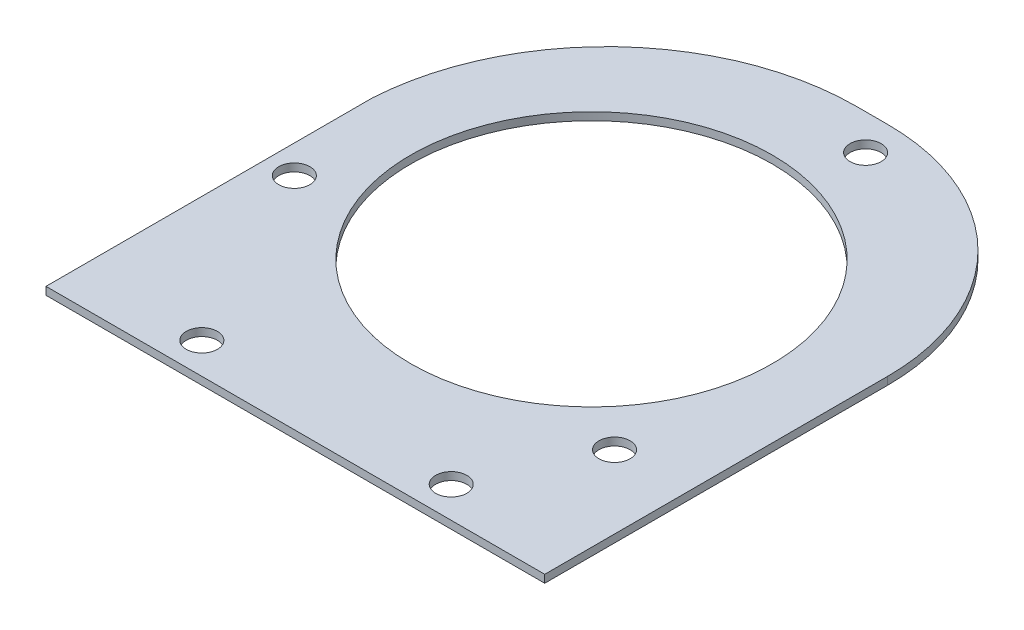
SolidWorks part; units mm, degrees
ref_plane "Front Plane" through (0, 0, 0) normal (0, 0, 1) x (1, 0, 0)
ref_plane "Top Plane" through (0, 0, 0) normal (0, 1, 0) x (1, 0, 0)
ref_plane "Right Plane" through (0, 0, 0) normal (1, 0, 0) x (0, 0, -1)
sketch "Sketch1" plane through (0, 0, 0) normal (0, 1, 0) x (1, 0, 0)
  line L0 (0, 114.3) -> (0, -114.3) construction
  line L1 (12.7, 114.3) -> (0, 114.3)
  line L2 (101.6, 25.4) -> (101.6, -114.3)
  line L3 (101.6, -114.3) -> (-101.6, -114.3)
  line L4 (-101.6, 18.6765) -> (-101.6, -114.3)
  line L5 (101.6, 114.3) -> (-101.6, -114.3) construction
  line L6 (101.6, -114.3) -> (-101.6, 114.3) construction
  line L7 (-101.6, 6.35) -> (101.6, 6.35) construction
  line L8 (0, 6.35) -> (-101.6, -28.6337) construction
  line L9 (-101.6, -101.6) -> (101.6, -101.6) construction
  circle A0 centre (0, 6.35) radius 73.66
  circle A1 centre (0, 6.35) radius 95.25 construction
  circle A2 centre (-90.0606, -24.6604) radius 6.35
  circle A3 centre (-50.8, -101.6) radius 6.35
  circle A4 centre (50.8, -101.6) radius 6.35
  circle A5 centre (18.1746, 99.85) radius 6.35
  circle A6 centre (71.8861, -56.1396) radius 6.35
  arc A7 (0, 114.3) -> (-101.6, 18.6765) centre (0, 12.5132) ccw
  arc A8 (12.7, 114.3) -> (101.6, 25.4) centre (12.7, 25.4) cw
  point P0 (0, 0)
  point P11 (0, 6.35)
  point P30 (0, 6.35)
  point P32 (0, 6.35)
  dimension "D3" = 147.32
  dimension "D5" = 190.5
  dimension "D6" = 12.7
  dimension "D7" = 12.7
  dimension "D8" = 12.7
  dimension "D11" = 88.9
  dimension "D1" = 228.6
  dimension "D2" = 120.65
  dimension "D4" = 19
  dimension "D9" = 50.8
  dimension "D10" = 203.2
extrude "Boss-Extrude1" add sketch "Sketch1" along normal blind 3.175
sketch "Sketch2" plane through (0, 3.175, 0) normal (0, 1, 0) x (1, 0, 0)
  line L0 (-101.6, 18.6765) -> (-101.6, -114.3) construction
  line L2 (101.6, -167.64) -> (-101.6, -167.64)
  line L5 (101.6, -167.64) -> (101.6, 114.3)
  line L6 (101.6, 114.3) -> (-101.6, 114.3)
  line L7 (-101.6, -114.3) -> (101.6, -114.3) construction
  line L8 (101.6, -114.3) -> (101.6, 25.4) construction
  line L9 (12.7, 114.3) -> (0, 114.3) construction
  line L10 (-101.6, 18.6765) -> (-101.6, -114.3)
  line L11 (-101.6, -114.3) -> (101.6, -114.3)
  line L12 (101.6, -114.3) -> (101.6, 25.4)
  line L13 (12.7, 114.3) -> (0, 114.3)
  line L14 (-101.6, -167.64) -> (-101.6, 114.3)
  line L15 (101.6, -167.64) -> (-139.7, -167.64)
  line L16 (101.6, -167.64) -> (101.6, 115.3414)
  line L17 (101.6, 115.3414) -> (-139.7, 115.3414)
  line L18 (-139.7, -167.64) -> (-139.7, 115.3414)
  point P0 (0, 0)
  dimension "D1" = 1.0414
  dimension "D2" = 53.34
  dimension "D3" = 228.6
  dimension "D4" = 203.2
  dimension "D5" = 241.3
  dimension "D6" = 282.9814
